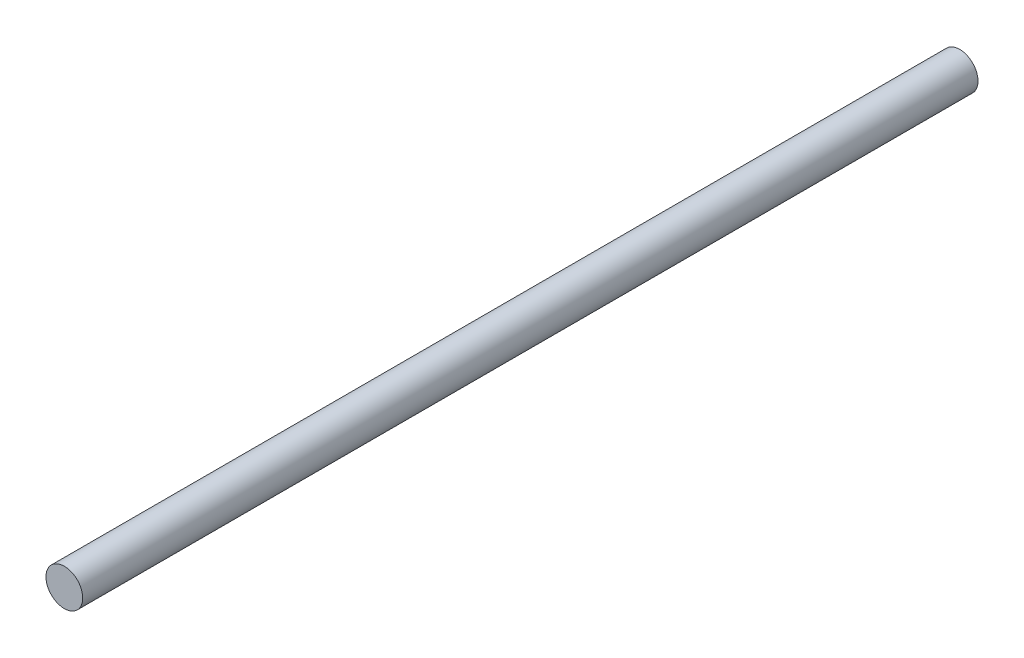
SolidWorks part; units mm, degrees
ref_plane "Alzado" through (0, 0, 0) normal (0, 0, 1) x (1, 0, 0)
ref_plane "Planta" through (0, 0, 0) normal (0, 1, 0) x (1, 0, 0)
ref_plane "Vista lateral" through (0, 0, 0) normal (1, 0, 0) x (0, 0, -1)
sketch "Croquis1" plane through (0, 0, 0) normal (0, 0, 1) x (1, 0, 0)
  circle A0 centre (0, 0) radius 4
  dimension "D1" = 8
extrude "Saliente-Extruir1" add sketch "Croquis1" along normal blind 195
cosmetic thread "Rosca cosmética1" parameters "D2"=6
